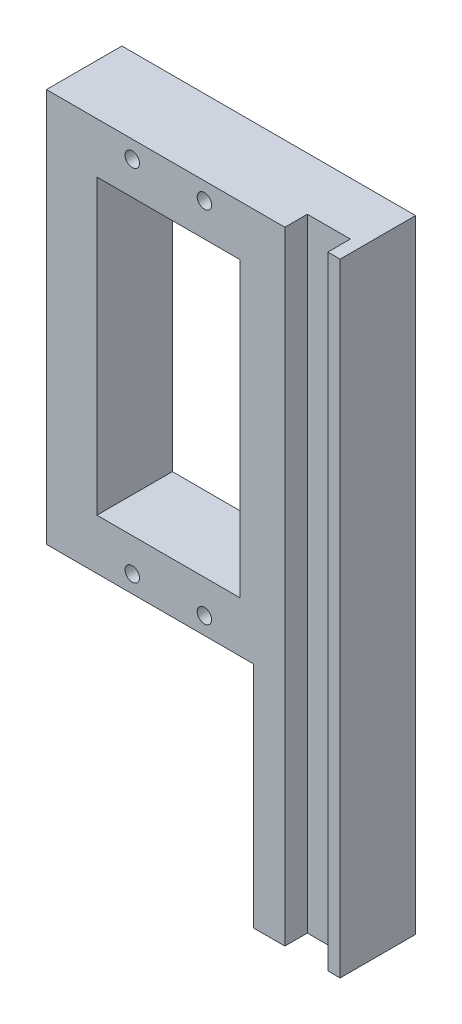
SolidWorks part; units mm, degrees
ref_plane "Front Plane" through (0, 0, 0) normal (0, 0, 1) x (1, 0, 0)
ref_plane "Top Plane" through (0, 0, 0) normal (0, 1, 0) x (1, 0, 0)
ref_plane "Right Plane" through (0, 0, 0) normal (1, 0, 0) x (0, 0, -1)
sketch "Sketch2" plane through (0, 0, 0) normal (0, 0, 1) x (1, 0, 0)
  line L0 (-9.9, -20.3) -> (9.9, -20.3)
  line L1 (9.9, -19.3) -> (9.9, -20.3)
  line L2 (9.9, -19.3) -> (9.9, 20.3)
  line L4 (9.9, 20.3) -> (-9.9, 20.3)
  line L7 (-9.9, 20.3) -> (-9.9, -20.3)
  line L9 (-7.9, 27.3) -> (23.8131, 27.3)
  line L10 (-7.9, 27.3) -> (-16.9, 27.3)
  line L11 (11.8131, -27.3) -> (11.8131, -59.0021)
  line L12 (-16.9, 27.3) -> (-16.9, -27.3)
  line L13 (-2.175, -27.3) -> (-16.9, -27.3)
  line L15 (-2.175, -27.3) -> (11.8131, -27.3)
  line L16 (11.8131, -59.0021) -> (23.8131, -59.0021)
  line L17 (23.8131, -59.0021) -> (23.8131, 27.3)
extrude "Boss-Extrude2" add sketch "Sketch2" along normal blind 10.46
sketch "Sketch4" plane through (0, 0, 10.46) normal (0, 0, 1) x (1, 0, 0)
  line L0 (17.8131, -59.0021) -> (17.2, -59.0021)
  line L1 (17.2, 27.3) -> (16.1509, 27.3)
  line L2 (23.8131, 27.3) -> (-16.9, 27.3) construction
  line L3 (16.1509, 27.3) -> (16.1509, -59.0021)
  line L4 (11.8131, -59.0021) -> (23.8131, -59.0021) construction
  line L5 (17.8131, -59.0021) -> (22.1131, -59.0021)
  line L6 (22.1131, -59.0021) -> (22.1131, 27.3)
  line L7 (22.1131, 27.3) -> (17.2, 27.3)
  line L8 (16.1509, -59.0021) -> (17.8131, -59.0021)
  line L9 (17.2, -59.0021) -> (16.1509, -59.0021)
extrude "Cut-Extrude1" cut sketch "Sketch4" against normal blind 3.12 contours L5 L6 L7 L1 L3 L9 L0
sketch "Sketch5" plane through (0, 0, 10.46) normal (0, 0, 1) x (1, 0, 0)
  circle A0 centre (-5, -24.9) radius 1
  circle A1 centre (5, -24.9) radius 1
  circle A2 centre (-5, 24.89) radius 1
  circle A3 centre (5, 24.89) radius 1
extrude "Cut-Extrude2" cut sketch "Sketch5" against normal blind 20
